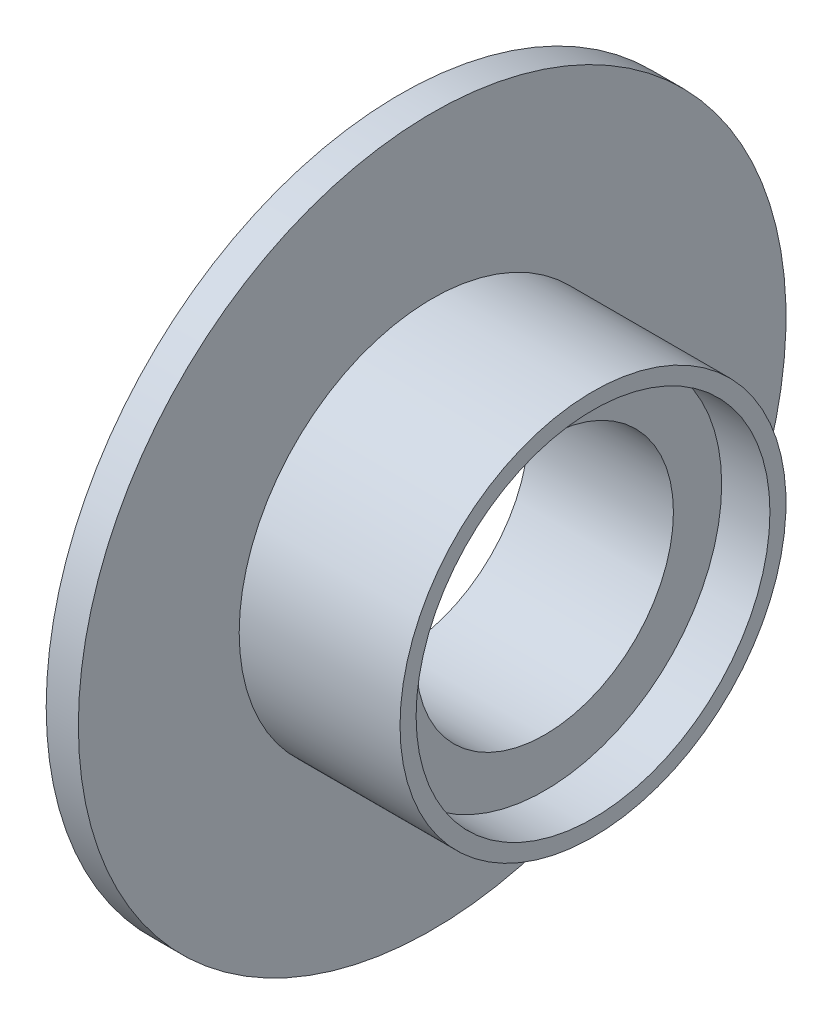
SolidWorks part; units mm, degrees
ref_plane "Front Plane" through (0, 0, 0) normal (0, 0, 1) x (1, 0, 0)
ref_plane "Top Plane" through (0, 0, 0) normal (0, 1, 0) x (1, 0, 0)
ref_plane "Right Plane" through (0, 0, 0) normal (1, 0, 0) x (0, 0, -1)
sketch "Sketch1" plane through (0, 0, 0) normal (0, 1, 0) x (1, 0, 0)
  line L0 (0, 0) -> (20.1962, 0) construction
  line L1 (0, 8) -> (0, 22)
  line L2 (0, 22) -> (2, 22)
  line L3 (2, 22) -> (2, 12)
  line L4 (2, 12) -> (12, 12)
  line L5 (12, 12) -> (12, 11)
  line L7 (9, 8) -> (0, 8)
  line L8 (12, 11) -> (9, 11)
  line L9 (9, 11) -> (9, 8)
  dimension "D1" = 44
  dimension "D2" = 24
  dimension "D3" = 2
  dimension "D4" = 10
  dimension "D5" = 16
  dimension "D6" = 22
  dimension "D7" = 3
revolve "Revolve1" add sketch "Sketch1" angle 360 about L0
move or copy body "Body-Move/Copy1" [suppressed] bodies to move or copy 101
